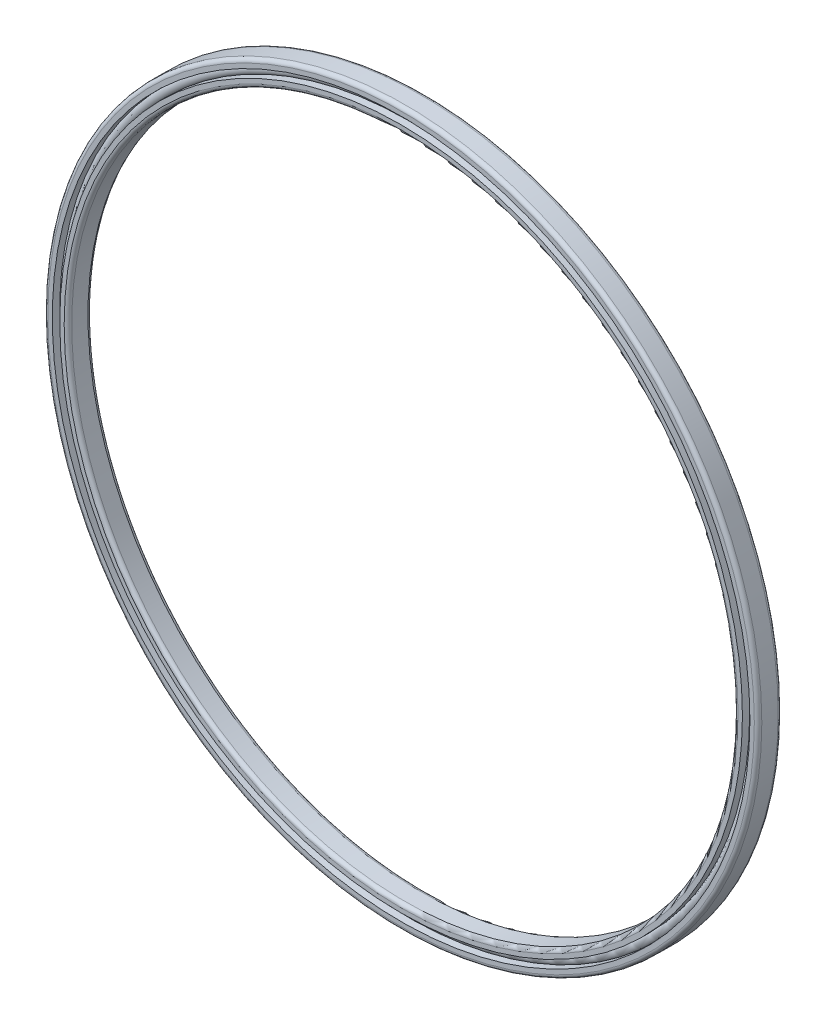
SolidWorks part; units mm, degrees
material "镀铬不锈钢"
ref_plane "前视基准面" through (0, 0, 0) normal (0, 0, 1) x (1, 0, 0)
ref_plane "上视基准面" through (0, 0, 0) normal (0, 1, 0) x (1, 0, 0)
ref_plane "右视基准面" through (0, 0, 0) normal (1, 0, 0) x (0, 0, -1)
other "Configuration Table"
sketch "草图1" plane through (0, 0, 0) normal (0, 1, 0) x (1, 0, 0)
  line L0 (0, 0) -> (0, 21.7626) construction
  line L1 (88.9, 1) -> (88.9, 5.35)
  line L2 (89.9, 6.35) -> (91.075, 6.35)
  line L3 (91.075, 6.35) -> (91.075, 4.4079)
  line L4 (91.075, 0) -> (89.9, 0)
  line L5 (93.075, 0) -> (93.075, 1.9421)
  line L6 (93.075, 6.35) -> (94.25, 6.35)
  line L7 (95.25, 5.35) -> (95.25, 1)
  line L8 (94.25, 0) -> (93.075, 0)
  line L9 (108.075, 6.35) -> (93.075, 6.35)
  line L10 (93.075, 4.4079) -> (93.075, 6.35)
  line L11 (91.075, 1.9421) -> (91.075, 0)
  line L31 (93.075, -4) -> (193.075, -4)
  line L32 (193.075, 0) -> (193.075, -4)
  line L38 (91.075, 0) -> (91.075, -4)
  line L42 (91.075, 6.35) -> (91.075, 10.35)
  line L46 (75.9, 0) -> (75.9, 6.1)
  line L49 (81.9, 10.35) -> (85.9, 10.35)
  line L50 (81.9, 10.35) -> (81.9, -4)
  line L51 (81.9, -4) -> (85.9, -4)
  line L52 (85.9, 10.35) -> (85.9, -4)
  line L54 (102.575, -4) -> (104.75, -4)
  line L64 (88.9, 0) -> (75.9, 0)
  line L65 (88.9, 0) -> (88.9, 6.1)
  line L66 (88.9, 6.1) -> (75.9, 6.1)
  line L67 (75.9, 0) -> (75.9, 6.1)
  line L69 (93.075, 9.35) -> (108.075, 9.35)
  line L70 (108.075, 6.35) -> (108.075, 9.35)
  line L71 (95.25, 0) -> (108.25, 0)
  line L72 (95.25, 0) -> (95.25, 6.1)
  line L73 (95.25, 6.1) -> (108.25, 6.1)
  line L74 (108.25, 0) -> (108.25, 6.1)
  line L75 (93.075, 6.35) -> (93.075, 9.35)
  line L76 (91.075, 6.35) -> (76.075, 6.35)
  line L77 (193.075, 0) -> (93.075, 0)
  line L78 (91.075, -4) -> (76.075, -4)
  line L79 (91.075, -4) -> (91.075, 0)
  line L80 (91.075, 0) -> (76.075, 0)
  line L81 (76.075, -4) -> (76.075, 0)
  line L82 (93.075, 0) -> (93.075, -4)
  line L83 (95.25, 3.175) -> (94.25, 3.175) construction
  line L84 (98.25, 9.35) -> (102.25, 9.35)
  line L85 (98.25, 9.35) -> (98.25, -4)
  line L86 (98.25, -4) -> (102.25, -4)
  line L87 (102.25, 9.35) -> (102.25, -4)
  line L88 (91.075, 6.35) -> (76.075, 6.35)
  line L89 (91.075, 6.35) -> (91.075, 10.35)
  line L90 (91.075, 10.35) -> (76.075, 10.35)
  line L91 (76.075, 6.35) -> (76.075, 10.35)
  circle A0 centre (92.075, 3.175) radius 1.5875
  arc A1 (94.25, 0) -> (95.25, 1) centre (94.25, 1) ccw
  arc A2 (95.25, 5.35) -> (94.25, 6.35) centre (94.25, 5.35) ccw
  arc A3 (88.9, 1) -> (89.9, 0) centre (89.9, 1) ccw
  arc A4 (88.9, 5.35) -> (89.9, 6.35) centre (89.9, 5.35) cw
  point P17 (95.25, 0)
  point P20 (95.25, 6.35)
  point P23 (88.9, 0)
  dimension "D5" = 3.175
  dimension "D6" = 1
  dimension "D7" = 1
  dimension "D2" = 190.5
  dimension "D3" = 177.8
  dimension "D4" = 2
  dimension "D8" = 100
  dimension "D9" = 15
  dimension "D10" = 3
  dimension "D11" = 6.1
  dimension "D12" = 13
  dimension "D13" = 13
  dimension "D14" = 6.1
  dimension "D15" = 4
  dimension "D16" = 6.35
  dimension "D17" = 4
  dimension "D18" = 4
  dimension "D19" = 15
  dimension "D20" = 4
  dimension "D21" = 6
  dimension "D22" = 6
  dimension "D23" = 15
  dimension "D24" = 4
  dimension "D25" = 184.15
revolve "旋转1" add sketch "草图1" angle 360 about L0
